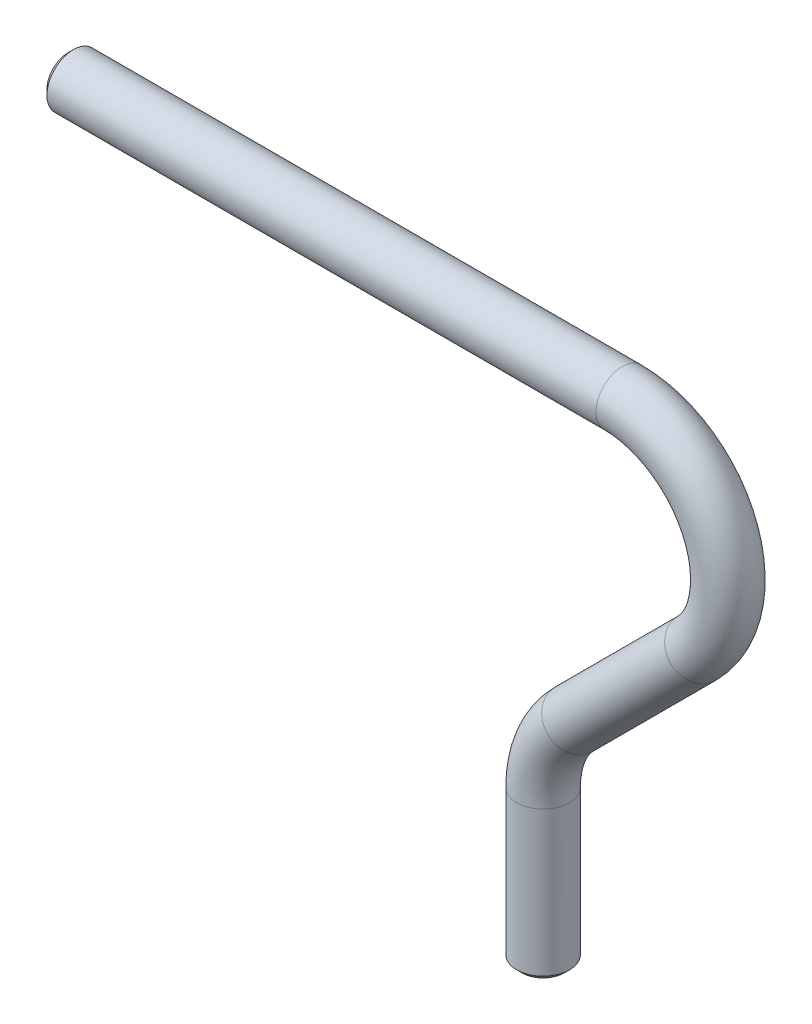
SolidWorks part; units mm, degrees
ref_plane "Front" through (0, 0, 0) normal (0, 0, 1) x (1, 0, 0)
ref_plane "Top" through (0, 0, 0) normal (0, 1, 0) x (1, 0, 0)
ref_plane "Right" through (0, 0, 0) normal (1, 0, 0) x (0, 0, -1)
sketch "Эскиз1" plane through (0, 0, 0) normal (0, 0, 1) x (1, 0, 0)
  line L0 (0, 0) -> (105, 0)
  line L1 (119.1421, -34.1421) -> (95.8579, -57.4264)
  line L2 (90, -71.5685) -> (90, -100)
  arc A0 (105, 0) -> (119.1421, -34.1421) centre (105, -20) cw
  arc A1 (95.8579, -57.4264) -> (90, -71.5685) centre (110, -71.5685) ccw
  dimension "D1" = 125
  dimension "D2" = 20
  dimension "D6" = 20
  dimension "D3" = 45
  dimension "D4" = 90
  dimension "D5" = 100
sketch "Чертеж детали" plane through (0, 0, 0) normal (0, 0, 1) x (1, 0, 0)
  line L0 (143.4282, 22.2122) -> (1796.7615, 22.2122) construction
sketch "Эскиз2" plane through (0, 0, 0) normal (1, 0, 0) x (0, 0, -1)
  circle A0 centre (0, 0) radius 5
  circle A1 centre (0, 0) radius 3
  dimension "D1" = 10
  dimension "D2" = 2
sweep "По траектории1" add profiles "Эскиз2" path "Эскиз1"
cosmetic thread "Условное изображение резьбы1"
cosmetic thread "Условное изображение резьбы2"
chamfer "Фаска1" distance 1 angle 45 2 edges at (90, -100, -5) (0, 0, -5)
